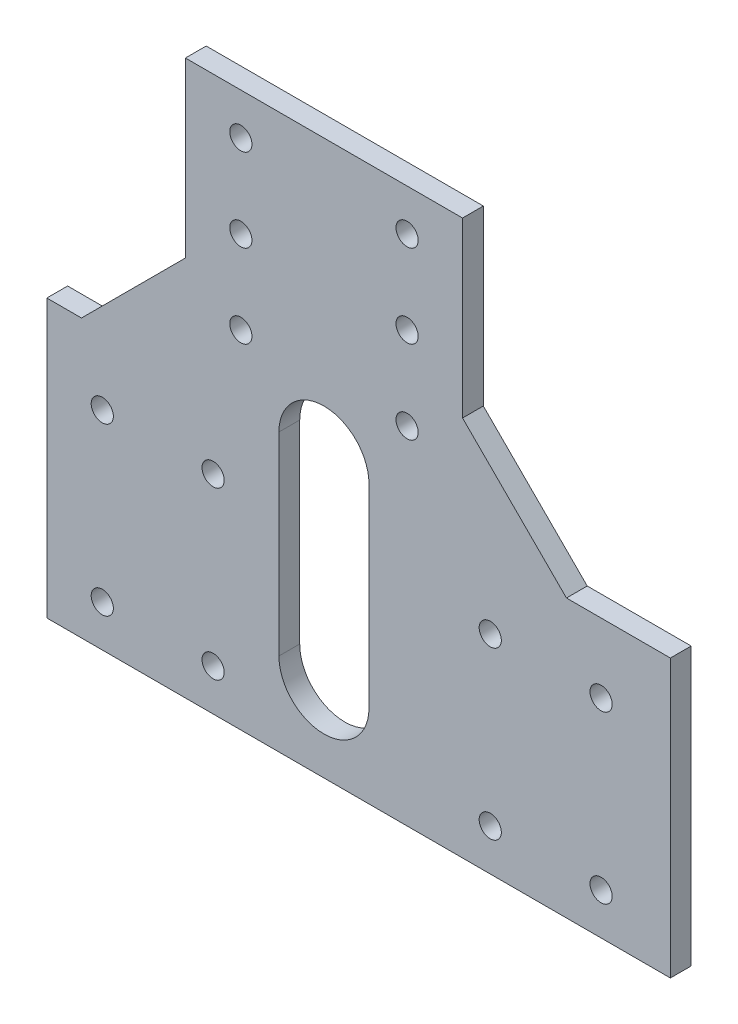
SolidWorks part; units mm, degrees
material "Thornel VCB-20 碳布"
ref_plane "前视基准面" through (0, 0, 0) normal (0, 0, 1) x (1, 0, 0)
ref_plane "上视基准面" through (0, 0, 0) normal (0, 1, 0) x (1, 0, 0)
ref_plane "右视基准面" through (0, 0, 0) normal (1, 0, 0) x (0, 0, -1)
other "Configuration Table"
sketch "草图1" plane through (0, 0, 0) normal (0, 0, 1) x (1, 0, 0)
  line L0 (0, 0) -> (0, 40)
  line L1 (0, 40) -> (5, 40)
  line L2 (5, 40) -> (20, 55)
  line L3 (20, 55) -> (20, 80)
  line L4 (20, 80) -> (60, 80)
  line L5 (60, 80) -> (60, 55)
  line L6 (60, 55) -> (75, 40)
  line L7 (75, 40) -> (90, 40)
  line L8 (90, 40) -> (90, 0)
  line L9 (90, 0) -> (0, 0)
  line L10 (60, 55) -> (20, 55) construction
  line L11 (20, 40) -> (5, 40) construction
  line L12 (20, 40) -> (20, 55) construction
  line L13 (60, 55) -> (60, 40) construction
  line L14 (60, 40) -> (75, 40)
  dimension "D1" = 45
  dimension "D2" = 40
  dimension "D3" = 45
  dimension "D4" = 40
  dimension "D5" = 20
  dimension "D6" = 5
  dimension "D7" = 40
  dimension "D8" = 30
extrude "凸台-拉伸1" add sketch "草图1" along normal blind 3
sketch "草图2" plane through (0, 0, 3) normal (0, 0, 1) x (1, 0, 0)
  line L0 (0, 40) -> (90, 40) construction
  line L1 (28, 74) -> (28, 50) construction
  line L2 (28, 50) -> (52, 50) construction
  line L3 (52, 50) -> (52, 74) construction
  line L4 (52, 74) -> (28, 74) construction
  line L5 (20, 55) -> (20, 80) construction
  line L6 (20, 80) -> (60, 80) construction
  line L7 (8, 30) -> (80, 30) construction
  line L8 (80, 30) -> (80, 6) construction
  line L9 (80, 6) -> (8, 6) construction
  line L10 (8, 6) -> (8, 30) construction
  line L11 (0, 0) -> (0, 40) construction
  line L12 (90, 40) -> (90, 0) construction
  line L13 (90, 0) -> (0, 0) construction
  line L14 (40, 40) -> (40, 12) construction
  line L17 (46.5, 40) -> (46.5, 12)
  line L18 (33.5, 40) -> (33.5, 12)
  circle A0 centre (28, 74) radius 1.6
  circle A1 centre (28, 50) radius 1.6
  circle A2 centre (52, 74) radius 1.6
  circle A3 centre (52, 50) radius 1.6
  circle A4 centre (8, 30) radius 1.6
  circle A5 centre (24, 30) radius 1.6
  circle A6 centre (80, 30) radius 1.6
  circle A7 centre (64, 30) radius 1.6
  circle A8 centre (80, 6) radius 1.6
  circle A9 centre (64, 6) radius 1.6
  circle A10 centre (24, 6) radius 1.6
  circle A11 centre (8, 6) radius 1.6
  arc A15 (46.5, 40) -> (33.5, 40) centre (40, 40) ccw
  arc A16 (33.5, 12) -> (46.5, 12) centre (40, 12) ccw
  circle A17 centre (28, 62) radius 1.6
  circle A18 centre (52, 62) radius 1.6
  point P40 (40, 26)
  dimension "D1" = 3.2
  dimension "D6" = 3.2
  dimension "D15" = 12
  dimension "D16" = 6.5
  dimension "D19" = 3.2
  dimension "D20" = 3.2
  dimension "D2" = 24
  dimension "D3" = 8
  dimension "D4" = 6
  dimension "D5" = 24
  dimension "D7" = 8
  dimension "D8" = 10
  dimension "D9" = 16
  dimension "D10" = 40
  dimension "D11" = 16
  dimension "D12" = 40
  dimension "D13" = 6
  dimension "D14" = 10
  dimension "D17" = 28
  dimension "D18" = 12
extrude "切除-拉伸1" cut sketch "草图2" against normal blind 3
